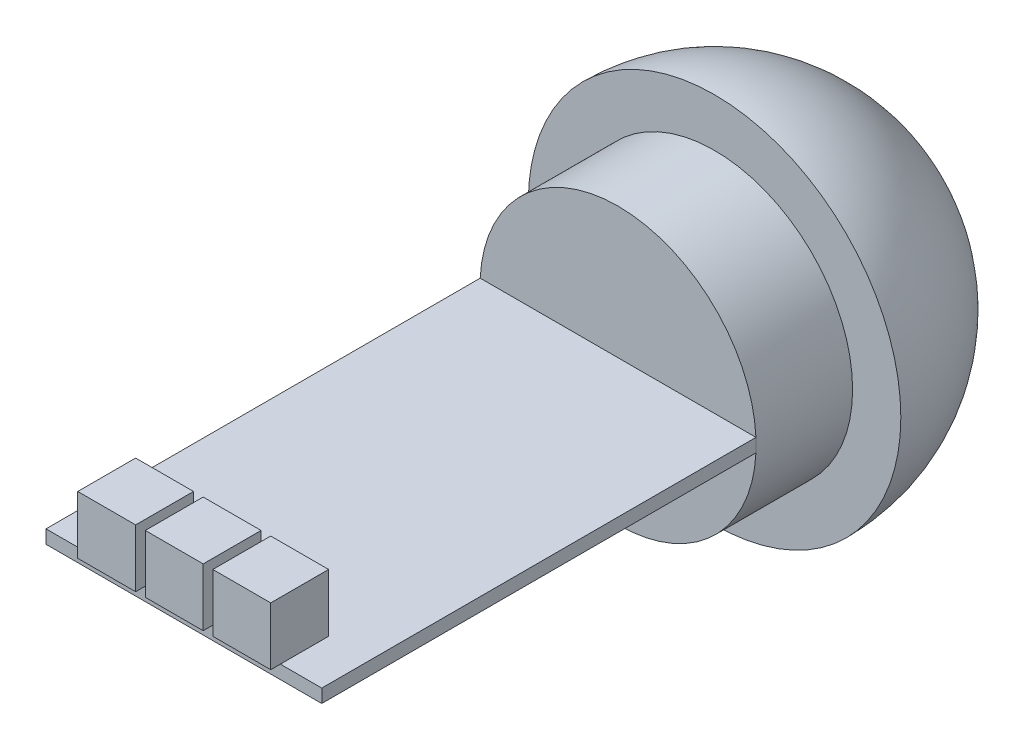
SolidWorks part; units mm, degrees
ref_plane "Front" through (0, 0, 0) normal (0, 0, 1) x (1, 0, 0)
ref_plane "Top" through (0, 0, 0) normal (0, 1, 0) x (1, 0, 0)
ref_plane "Right" through (0, 0, 0) normal (1, 0, 0) x (0, 0, -1)
sketch "Sketch1" plane through (0, 0, 0) normal (0, 1, 0) x (1, 0, 0)
  line L0 (19.3064, 0) -> (0, 0)
  line L1 (0, 0) -> (0, 19.3064)
  arc A0 (0, 19.3064) -> (19.3064, 0) centre (0, 0) cw
revolve "Revolve1" add sketch "Sketch1" angle 360 about L1
sketch "Sketch2" plane through (0, 0, 0) normal (0, 0, 1) x (1, 0, 0)
  circle A2 centre (0, 0) radius 14.3064
  circle A3 centre (0, 0) radius 14.3064
  dimension "D1" = 5
extrude "Boss-Extrude1" add sketch "Sketch2" along normal blind 10
sketch "Sketch3" plane through (0, 0, 10) normal (0, 0, 1) x (1, 0, 0)
  line L1 (-14.2895, -0.695) -> (14.2895, -0.695)
  line L2 (-14.2895, -0.695) -> (-14.2895, 0.695)
  line L3 (-14.2895, 0.695) -> (14.2895, 0.695)
  line L4 (14.2895, -0.695) -> (14.2895, 0.695)
  line L5 (-14.2895, -0.695) -> (14.2895, 0.695) construction
  line L6 (-14.2895, 0.695) -> (14.2895, -0.695) construction
  circle A0 centre (0, 0) radius 14.3064 construction
  point P0 (0, 0)
extrude "Boss-Extrude2" add sketch "Sketch3" along normal blind 45
sketch "Sketch4" plane through (0, 0.695, 0) normal (0, 1, 0) x (1, 0, 0)
  line L0 (4, -50) -> (10, -50)
  line L1 (-3, -50) -> (3, -50)
  line L2 (-3, -50) -> (-3, -56)
  line L3 (-3, -56) -> (3, -56)
  line L4 (3, -50) -> (3, -56)
  line L5 (4, -50) -> (4, -56)
  line L6 (4, -56) -> (10, -56)
  line L7 (10, -50) -> (10, -56)
  line L8 (-10, -50) -> (-4, -50)
  line L9 (-10, -50) -> (-10, -56)
  line L10 (-10, -56) -> (-4, -56)
  line L11 (-4, -50) -> (-4, -56)
  line L12 (-4, -56) -> (-3, -56) construction
  line L13 (3, -56) -> (4, -56) construction
  line L14 (14.2895, -10) -> (-14.2895, -10) construction
  line L15 (-14.2895, -55) -> (14.2895, -55) construction
  point P14 (0, -50)
  point P17 (0, -10)
  dimension "D1" = 1
  dimension "D2" = 6
  dimension "D3" = 1
extrude "Boss-Extrude3" add sketch "Sketch4" along normal blind 6
